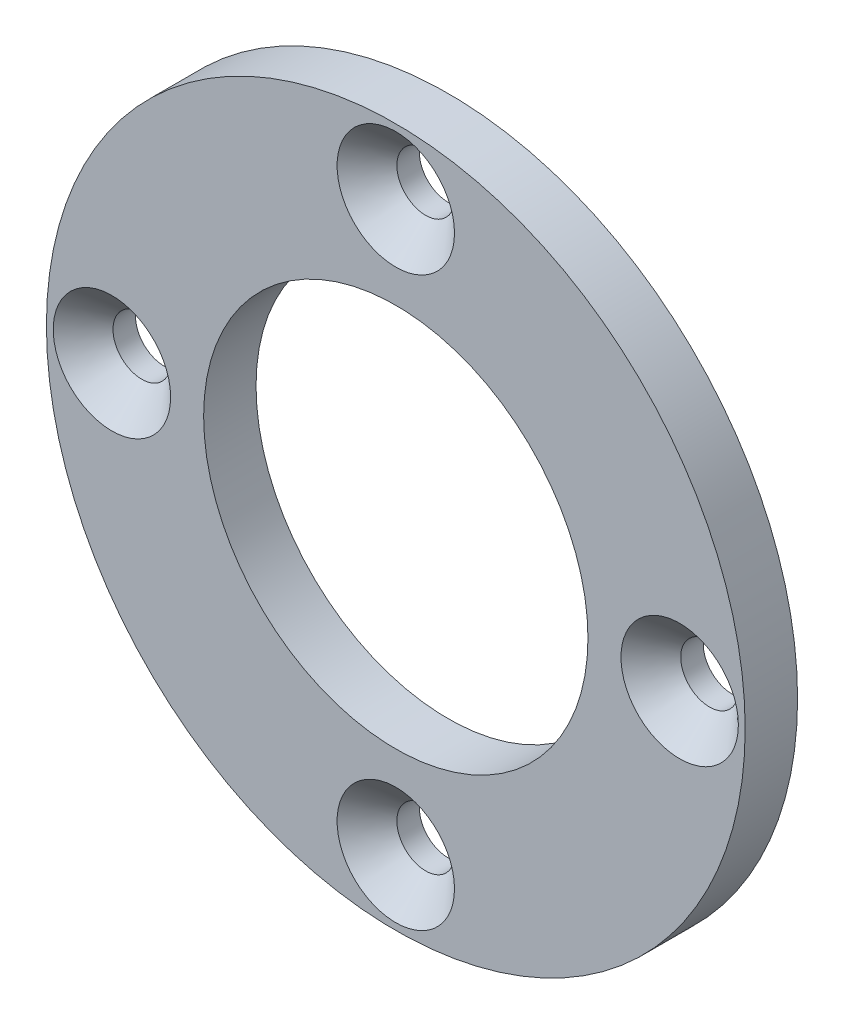
SolidWorks part; units mm, degrees
ref_plane "Front Plane" through (0, 0, 0) normal (0, 0, 1) x (1, 0, 0)
ref_plane "Top Plane" through (0, 0, 0) normal (0, 1, 0) x (1, 0, 0)
ref_plane "Right Plane" through (0, 0, 0) normal (1, 0, 0) x (0, 0, -1)
sketch "Sketch1" plane through (0, 0, 0) normal (0, 0, 1) x (1, 0, 0)
  circle A0 centre (0, 0) radius 40
  circle A1 centre (0, 0) radius 22
  dimension "D1" = 80
  dimension "D2" = 44
extrude "Boss-Extrude1" add sketch "Sketch1" along normal blind 6
sketch "Sketch2" plane through (0, 0, 6) normal (0, 0, 1) x (1, 0, 0)
  circle A0 centre (0, 0) radius 32.5 construction
  dimension "D1" = 65
sketch "Sketch3" plane through (0, 0, 6) normal (0, 0, 1) x (1, 0, 0)
  line L0 (-40, 0) -> (40, 0) construction
  line L1 (0, -40) -> (0, 40) construction
  circle A0 centre (0, 0) radius 40 construction
  point P7 (0, 0)
  point P11 (0, 0)
hole_wizard "CSK for M5 Countersunk Flat Head Screw1" positions "Sketch5" profile "Sketch6" countersink size "M5" standard "ISO" end condition through all
sketch "Sketch5" plane through (0, 0, 6) normal (0, 0, 1) x (1, 0, 0)
  line L0 (0, -40) -> (0, 40) construction
  line L1 (-40, 0) -> (40, 0) construction
  circle A0 centre (0, 0) radius 32.5 construction
  point P0 (0, 32.5)
  point P4 (-32.5, 0)
  point P6 (0, -32.5)
  point P10 (32.5, 0)
sketch "Sketch6" plane through (0, 32.5, 6) normal (1, 0, 0) x (0, -1, 0)
  line L0 (0, 0) -> (0, 6)
  line L1 (0, 6) -> (3.3, 6)
  line L2 (3.3, 6) -> (3.3, 3.42)
  line L3 (3.3, 3.42) -> (6.72, 0)
  line L5 (6.72, 0) -> (0, 0)
  line L6 (-3.3, 3.42) -> (-6.72, 0) construction
  line L11 (0, -6.35) -> (0, 107.95) construction
  dimension "Thru Hole Dia." = 6.6
  dimension "Thru Hole Depth" = 6
  dimension "Near C'Sink Dia." = 13.44
  dimension "Near C'Sink Angle" = 90
